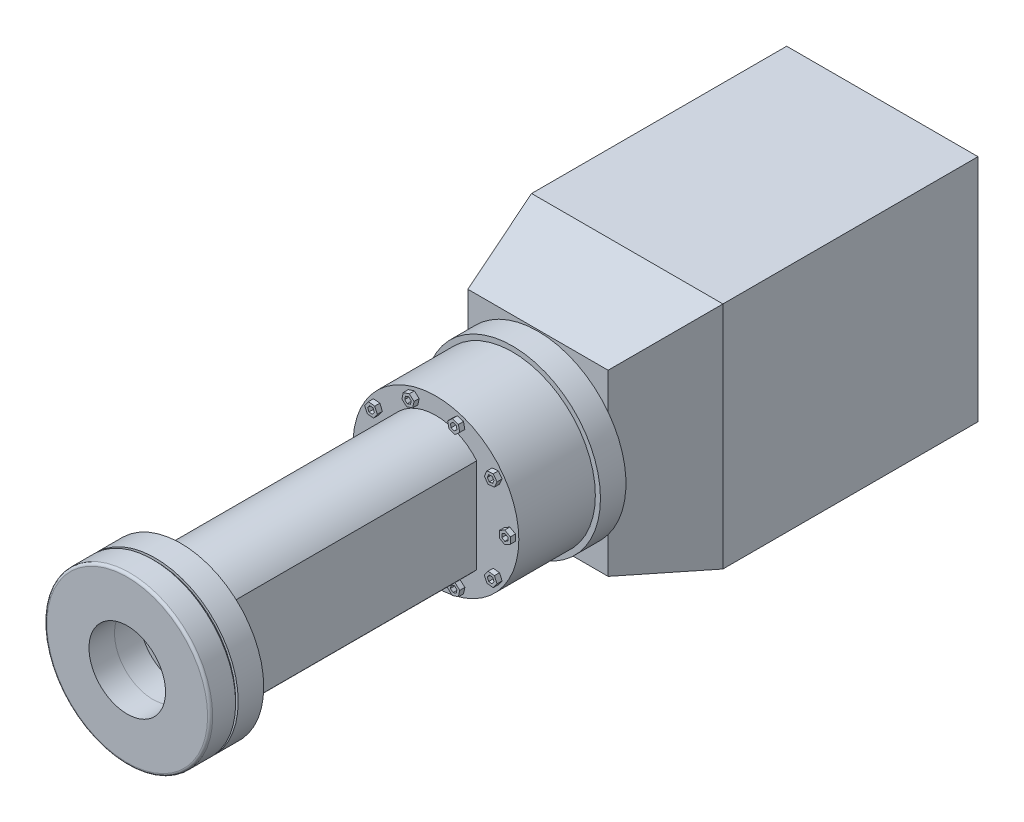
SolidWorks part; units mm, degrees
ref_plane "Front Plane" through (0, 0, 0) normal (0, 0, 1) x (1, 0, 0)
ref_plane "Top Plane" through (0, 0, 0) normal (0, 1, 0) x (1, 0, 0)
ref_plane "Right Plane" through (0, 0, 0) normal (1, 0, 0) x (0, 0, -1)
sketch "Sketch1" plane through (0, 0, 0) normal (0, 0, 1) x (1, 0, 0)
  line L0 (0, -45) -> (0, 45) construction
  line L1 (-37.5, 45) -> (37.5, 45)
  line L2 (-37.5, -45) -> (37.5, -45)
  line L3 (37.5, -45) -> (37.5, 45)
  line L4 (-37.5, -45) -> (-37.5, 45)
  point P4 (0, 0)
  point P7 (0, 45)
  point P10 (0, -45)
  dimension "D1" = 90
  dimension "D2" = 75
  dimension "D3" = 75
extrude "Boss-Extrude1" add sketch "Sketch1" along normal blind 100
sketch "Sketch2" plane through (0, 0, 100) normal (0, 0, 1) x (1, 0, 0)
  line L2 (37.5, 45) -> (-37.5, 45)
  line L3 (-37.5, -45) -> (37.5, -45)
  line L4 (37.5, 45) -> (-37.5, 45)
  line L5 (-37.5, -45) -> (37.5, -45)
  line L8 (37.5, -45) -> (37.5, 45)
  line L9 (37.5, -45) -> (37.5, 45)
  line L10 (-37.5, 45) -> (-37.5, -45)
  line L11 (-37.5, 45) -> (-37.5, -45)
  dimension "D1" = 0
ref_plane "Plane1" through (0, 0, 135) normal (0, 0, 1) x (1, 0, 0)
sketch "Sketch3" plane through (0, 0, 135) normal (0, 0, 1) x (1, 0, 0)
  line L4 (27.5, 35) -> (-27.5, 35)
  line L5 (-27.5, -35) -> (27.5, -35)
  line L6 (27.5, 35) -> (-27.5, 35)
  line L7 (-27.5, -35) -> (27.5, -35)
  line L8 (-27.5, 35) -> (-27.5, -35)
  line L9 (-27.5, 35) -> (-27.5, -35)
  line L10 (27.5, -35) -> (27.5, 35)
  line L11 (27.5, -35) -> (27.5, 35)
  dimension "D1" = 10
loft "Loft1" add profiles "Sketch3", "Sketch2"
sketch "Sketch4" plane through (0, 0, 135) normal (0, 0, 1) x (1, 0, 0)
  circle A0 centre (0, 0) radius 34.5
  dimension "D1" = 69
extrude "Boss-Extrude2" add sketch "Sketch4" along normal blind 10
sketch "Sketch5" plane through (0, 0, 145) normal (0, 0, 1) x (1, 0, 0)
  circle A2 centre (0, 0) radius 32.5
  circle A3 centre (0, 0) radius 32.5
  dimension "D1" = 2
extrude "Boss-Extrude3" add sketch "Sketch5" along normal blind 30
sketch "Sketch6" plane through (0, 0, 175) normal (0, 0, 1) x (1, 0, 0)
  line L0 (0, 0) -> (29, 0) construction
  line L1 (29, 1.3453) -> (27.8349, 0.6726)
  line L2 (29, 2.5) -> (26.8349, 1.25)
  line L3 (26.8349, 1.25) -> (26.8349, -1.25)
  line L4 (26.8349, -1.25) -> (29, -2.5)
  line L5 (29, -2.5) -> (31.1651, -1.25)
  line L6 (31.1651, -1.25) -> (31.1651, 1.25)
  line L7 (31.1651, 1.25) -> (29, 2.5)
  line L8 (27.8349, 0.6726) -> (27.8349, -0.6726)
  line L9 (27.8349, -0.6726) -> (29, -1.3453)
  line L10 (29, -1.3453) -> (30.1651, -0.6726)
  line L11 (30.1651, -0.6726) -> (30.1651, 0.6726)
  line L12 (30.1651, 0.6726) -> (29, 1.3453)
  circle A0 centre (29, 0) radius 2.1651 construction
  dimension "D1" = 29
  dimension "D2" = 5
  dimension "D3" = 1
extrude "Boss-Extrude4" add sketch "Sketch6" along normal blind 2
pattern_circular "CirPattern1" count 10 over 360 about axis through (0, 0, 0) along (0, 0, 1) of "Boss-Extrude4"
sketch "Sketch7" plane through (0, 0, 175) normal (0, 0, 1) x (1, 0, 0)
  line L0 (0, 0) -> (16, 0) construction
  line L1 (0, 0) -> (0, 21.2483) construction
  line L2 (0, 0) -> (0, -18.7463) construction
  line L3 (16, -18.5) -> (16, 18.5)
  line L4 (-16, -18.5) -> (-16, 18.5)
  arc A0 (-16, 18.5) -> (16, 18.5) centre (0, 4.8985) cw
  arc A1 (-16, -18.5) -> (16, -18.5) centre (0, -4.8985) ccw
  point P8 (16, 0)
  dimension "D3" = 21
  dimension "D1" = 37
  dimension "D2" = 32
extrude "Boss-Extrude5" add sketch "Sketch7" along normal blind 100
sketch "Sketch8" plane through (0, 0, 275) normal (0, 0, 1) x (1, 0, 0)
  circle A0 centre (0, 0) radius 32.5 construction
  circle A1 centre (0, 0) radius 32.5
extrude "Boss-Extrude6" add sketch "Sketch8" along normal blind 10
sketch "Sketch9" plane through (0, 0, 285) normal (0, 0, 1) x (1, 0, 0)
  circle A2 centre (0, 0) radius 31.5
  circle A3 centre (0, 0) radius 31.5
  dimension "D1" = 1
extrude "Boss-Extrude7" add sketch "Sketch9" along normal blind 1
sketch "Sketch10" plane through (0, 0, 286) normal (0, 0, 1) x (1, 0, 0)
  circle A1 centre (0, 0) radius 32.5 construction
  circle A4 centre (0, 0) radius 32.5
extrude "Boss-Extrude8" add sketch "Sketch10" along normal blind 10 separate body
ref_plane "Plane2" through (-37.5, 0, 0) normal (1, 0, 0) x (0, 0, -1)
fillet "Fillet2" radius 1 1 edges at (32.5, 0, 296)
sketch "Sketch15" plane through (0, 0, 296) normal (0, 0, 1) x (1, 0, 0)
  circle A0 centre (0, 0) radius 15
  dimension "D1" = 30
extrude "Cut-Extrude2" cut sketch "Sketch15" against normal blind 20
sketch "Sketch16" plane through (0, 0, 0) normal (1, 0, 0) x (0, 0, -1)
  circle A0 centre (-36.9914, 0) radius 15
extrude "Cut-Extrude3" cut sketch "Sketch16" against normal blind 20 from offset 17.5
